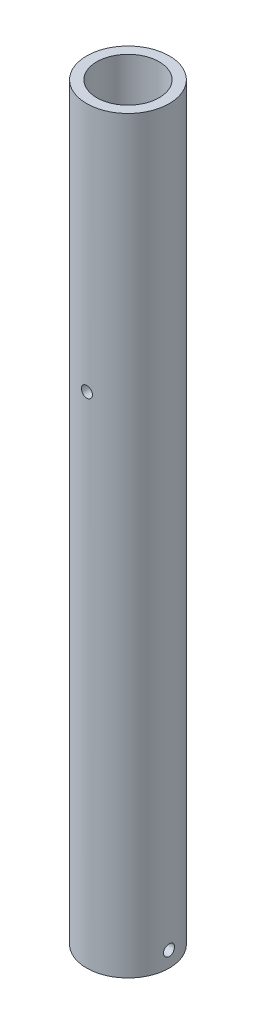
SolidWorks part; units mm, degrees
material "PVC Rigid"
ref_plane "Front Plane" through (0, 0, 0) normal (0, 0, 1) x (1, 0, 0)
ref_plane "Top Plane" through (0, 0, 0) normal (0, 1, 0) x (1, 0, 0)
ref_plane "Right Plane" through (0, 0, 0) normal (1, 0, 0) x (0, 0, -1)
sketch "Sketch1" plane through (0, 0, 0) normal (0, 1, 0) x (1, 0, 0)
  circle A0 centre (0, 0) radius 12.7
  circle A1 centre (0, 0) radius 16.8275
  dimension "D1" = 33.655
  dimension "D2" = 25.4
extrude "Boss-Extrude1" add sketch "Sketch1" along normal blind 304.8
sketch "Sketch2" plane through (0, 0, 0) normal (0, 0, 1) x (1, 0, 0)
  line L0 (0, 304.8) -> (0, 0) construction
  line L1 (12.7, 304.8) -> (-12.7, 304.8) construction
  line L2 (16.8275, 304.8) -> (-16.8275, 304.8) construction
  circle A0 centre (0, 203.2) radius 2.2479
  dimension "D1" = 4.4958
  dimension "D2" = 101.6
extrude "Cut-Extrude1" cut sketch "Sketch2" against normal through all both and the other way through all
sketch "Sketch3" plane through (0, 0, 0) normal (1, 0, 0) x (0, 0, -1)
  line L0 (0, 0) -> (0, 304.8) construction
  line L1 (16.8275, 304.8) -> (-16.8275, 304.8) construction
  line L2 (-16.8275, 0) -> (16.8275, 0) construction
  circle A0 centre (0, 6.35) radius 2.2479
  dimension "D1" = 4.4958
  dimension "D2" = 6.35
extrude "Cut-Extrude2" cut sketch "Sketch3" against normal through all both and the other way through all
